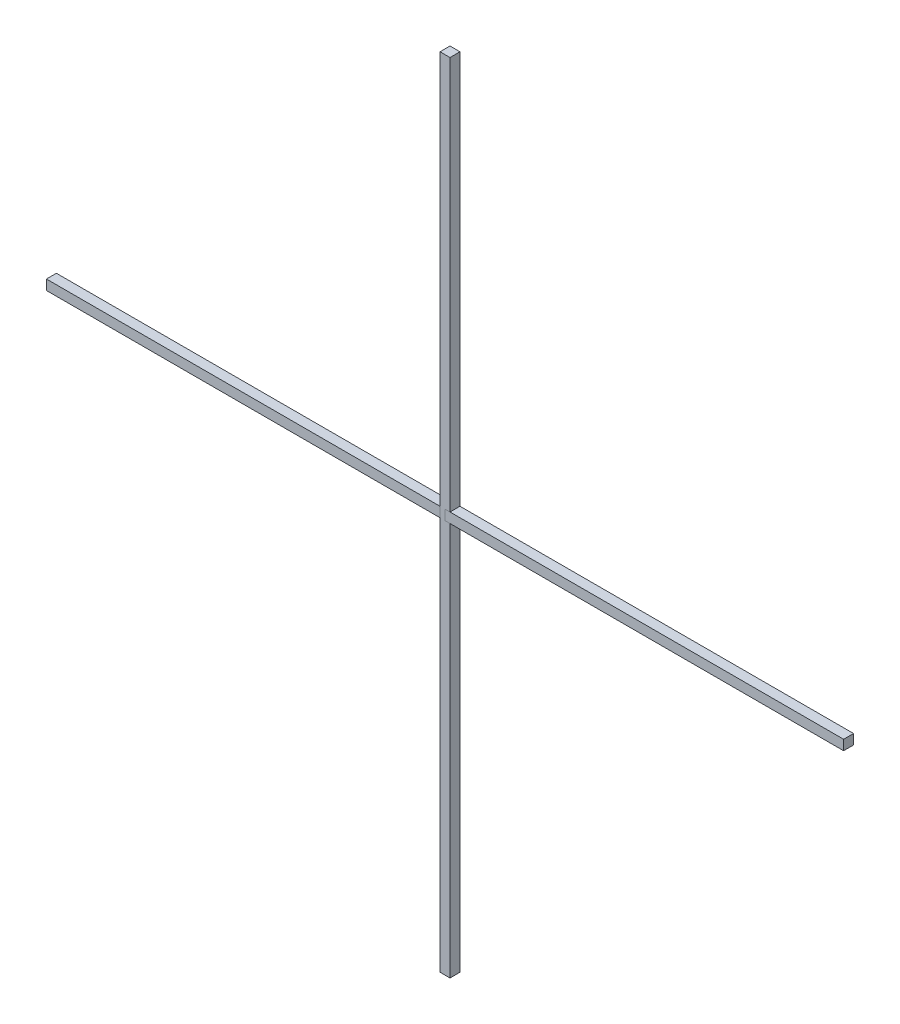
SolidWorks part; units mm, degrees
ref_plane "Front Plane" through (0, 0, 0) normal (0, 0, 1) x (1, 0, 0)
ref_plane "Top Plane" through (0, 0, 0) normal (0, 1, 0) x (1, 0, 0)
ref_plane "Right Plane" through (0, 0, 0) normal (1, 0, 0) x (0, 0, -1)
other "Configuration Table"
sketch "Sketch1" plane through (0, 0, 0) normal (0, 0, 1) x (1, 0, 0)
  line L0 (-5000, 0) -> (5000, 0)
  line L1 (55, 0) -> (-55, 0) construction
  line L3 (0, -1892.993) -> (0, 1892.993) construction
  line L4 (0, -5000) -> (0, 5000)
  dimension "D1" = 5000
  dimension "D2" = 5000
  dimension "D3" = 5000
  dimension "D4" = 5000
other "Structural Member1"
ref_plane "Plane1" through (-5000, 0, 0) normal (1, 0, 0) x (0, 1, 0)
sketch "Sketch11" plane through (-5000, 0, 0) normal (1, 0, 0) x (0, 1, 0)
  line L1 (62.5, -62.5) -> (-62.5, -62.5)
  line L2 (62.5, -62.5) -> (62.5, 62.5)
  line L3 (62.5, 62.5) -> (-62.5, 62.5)
  line L4 (-62.5, -62.5) -> (-62.5, 62.5)
  line L5 (62.5, -62.5) -> (-62.5, 62.5) construction
  line L6 (62.5, 62.5) -> (-62.5, -62.5) construction
  point P0 (0, 0)
  point P2 (0, 0)
  dimension "D2" = 125
  dimension "D1" = 125
other "Structural Member2"
ref_plane "Plane2" through (0, -5000, 0) normal (0, 1, 0) x (-1, 0, 0)
sketch "Sketch12" plane through (0, -5000, 0) normal (0, 1, 0) x (-1, 0, 0)
  line L1 (62.5, -62.5) -> (-62.5, -62.5)
  line L2 (62.5, -62.5) -> (62.5, 62.5)
  line L3 (62.5, 62.5) -> (-62.5, 62.5)
  line L4 (-62.5, -62.5) -> (-62.5, 62.5)
  line L5 (62.5, -62.5) -> (-62.5, 62.5) construction
  line L6 (62.5, 62.5) -> (-62.5, -62.5) construction
  point P0 (0, 0)
  point P2 (0, 0)
  dimension "D2" = 125
  dimension "D1" = 125
